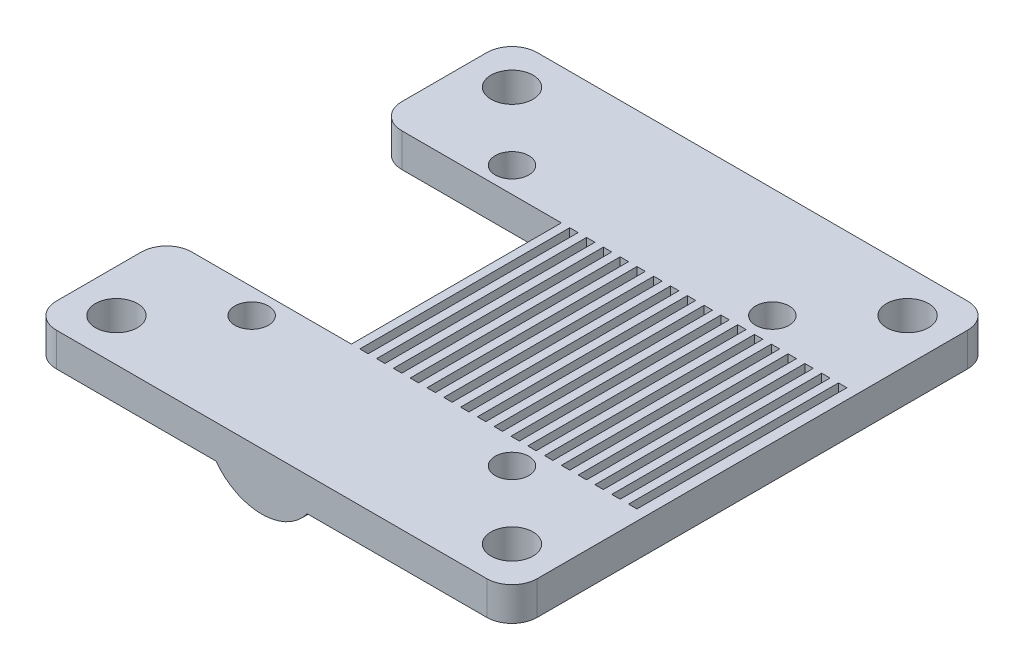
SolidWorks part; units mm, degrees
material "ABS"
ref_plane "Front Plane" through (0, 0, 0) normal (0, 0, 1) x (1, 0, 0)
ref_plane "Top Plane" through (0, 0, 0) normal (0, 1, 0) x (1, 0, 0)
ref_plane "Right Plane" through (0, 0, 0) normal (1, 0, 0) x (0, 0, -1)
sketch "Sketch1" plane through (0, 0, 0) normal (0, 1, 0) x (1, 0, 0)
  line L1 (25.625, 28.625) -> (-25.625, 28.625)
  line L2 (28.625, 25.625) -> (28.625, -25.625)
  line L3 (25.625, -28.625) -> (-25.625, -28.625)
  line L4 (-28.625, 25.625) -> (-28.625, -25.625)
  line L5 (28.625, 28.625) -> (-28.625, -28.625) construction
  line L6 (28.625, -28.625) -> (-28.625, 28.625) construction
  line L7 (23.55, -23.55) -> (-23.55, -23.55) construction
  line L8 (23.55, -23.55) -> (23.55, 23.55) construction
  line L9 (23.55, 23.55) -> (-23.55, 23.55) construction
  line L10 (-23.55, -23.55) -> (-23.55, 23.55) construction
  line L11 (23.55, -23.55) -> (-23.55, 23.55) construction
  line L12 (23.55, 23.55) -> (-23.55, -23.55) construction
  line L13 (15.5, 15.5) -> (-15.5, 15.5) construction
  line L14 (15.5, 15.5) -> (15.5, -15.5) construction
  line L15 (15.5, -15.5) -> (-15.5, -15.5) construction
  line L16 (-15.5, 15.5) -> (-15.5, -15.5) construction
  line L17 (15.5, 15.5) -> (-15.5, -15.5) construction
  line L18 (15.5, -15.5) -> (-15.5, 15.5) construction
  circle A0 centre (-15.5, 15.5) radius 2
  circle A1 centre (-23.55, 23.55) radius 2.5
  circle A2 centre (23.55, 23.55) radius 2.5
  circle A3 centre (15.5, 15.5) radius 2
  circle A4 centre (15.5, -15.5) radius 2
  circle A5 centre (-15.5, -15.5) radius 2
  circle A6 centre (-23.55, -23.55) radius 2.5
  circle A7 centre (23.55, -23.55) radius 2.5
  arc A8 (25.625, 28.625) -> (28.625, 25.625) centre (25.625, 25.625) cw
  arc A9 (28.625, -25.625) -> (25.625, -28.625) centre (25.625, -25.625) cw
  arc A10 (-25.625, -28.625) -> (-28.625, -25.625) centre (-25.625, -25.625) cw
  arc A11 (-25.625, 28.625) -> (-28.625, 25.625) centre (-25.625, 25.625) ccw
  point P0 (0, 0)
  point P5 (0, 0)
  point P11 (0, 0)
  dimension "D7" = 5
  dimension "D8" = 5
  dimension "D9" = 4
  dimension "D10" = 4
  dimension "D11" = 4
  dimension "D12" = 4
  dimension "D13" = 5
  dimension "D14" = 5
  dimension "D15" = 3
  dimension "D1" = 57.25
  dimension "D2" = 57.25
  dimension "D3" = 47.1
  dimension "D4" = 47.1
  dimension "D5" = 31
  dimension "D6" = 31
extrude "Boss-Extrude1" add sketch "Sketch1" along normal blind 4
sketch "Sketch2" plane through (0, 4, 0) normal (0, 1, 0) x (1, 0, 0)
  line L0 (-28.625, 25.625) -> (-28.625, -25.625) construction
  line L3 (-27.625, 12.5) -> (-26.625, 12.5)
  line L4 (-27.625, 12.5) -> (-27.625, -12.5)
  line L5 (-27.625, -12.5) -> (-26.625, -12.5)
  line L6 (-26.625, 12.5) -> (-26.625, -12.5)
  line L7 (-25.625, -12.5) -> (-24.625, -12.5)
  line L8 (-24.625, 12.5) -> (-24.625, -12.5)
  line L9 (-25.625, 12.5) -> (-25.625, -12.5)
  line L10 (-25.625, 12.5) -> (-24.625, 12.5)
  line L11 (-23.625, -12.5) -> (-22.625, -12.5)
  line L12 (-22.625, 12.5) -> (-22.625, -12.5)
  line L13 (-23.625, 12.5) -> (-23.625, -12.5)
  line L14 (-23.625, 12.5) -> (-22.625, 12.5)
  line L15 (-21.625, -12.5) -> (-20.625, -12.5)
  line L16 (-20.625, 12.5) -> (-20.625, -12.5)
  line L17 (-21.625, 12.5) -> (-21.625, -12.5)
  line L18 (-21.625, 12.5) -> (-20.625, 12.5)
  line L19 (-19.625, -12.5) -> (-18.625, -12.5)
  line L20 (-18.625, 12.5) -> (-18.625, -12.5)
  line L21 (-19.625, 12.5) -> (-19.625, -12.5)
  line L22 (-19.625, 12.5) -> (-18.625, 12.5)
  line L23 (-17.625, -12.5) -> (-16.625, -12.5)
  line L24 (-16.625, 12.5) -> (-16.625, -12.5)
  line L25 (-17.625, 12.5) -> (-17.625, -12.5)
  line L26 (-17.625, 12.5) -> (-16.625, 12.5)
  line L27 (-15.625, -12.5) -> (-14.625, -12.5)
  line L28 (-14.625, 12.5) -> (-14.625, -12.5)
  line L29 (-15.625, 12.5) -> (-15.625, -12.5)
  line L30 (-15.625, 12.5) -> (-14.625, 12.5)
  line L31 (-13.625, -12.5) -> (-12.625, -12.5)
  line L32 (-12.625, 12.5) -> (-12.625, -12.5)
  line L33 (-13.625, 12.5) -> (-13.625, -12.5)
  line L34 (-13.625, 12.5) -> (-12.625, 12.5)
  line L35 (-11.625, -12.5) -> (-10.625, -12.5)
  line L36 (-10.625, 12.5) -> (-10.625, -12.5)
  line L37 (-11.625, 12.5) -> (-11.625, -12.5)
  line L38 (-11.625, 12.5) -> (-10.625, 12.5)
  line L39 (-9.625, -12.5) -> (-8.625, -12.5)
  line L40 (-8.625, 12.5) -> (-8.625, -12.5)
  line L41 (-9.625, 12.5) -> (-9.625, -12.5)
  line L42 (-9.625, 12.5) -> (-8.625, 12.5)
  line L43 (-7.625, -12.5) -> (-6.625, -12.5)
  line L44 (-6.625, 12.5) -> (-6.625, -12.5)
  line L45 (-7.625, 12.5) -> (-7.625, -12.5)
  line L46 (-7.625, 12.5) -> (-6.625, 12.5)
  line L47 (-5.625, -12.5) -> (-4.625, -12.5)
  line L48 (-4.625, 12.5) -> (-4.625, -12.5)
  line L49 (-5.625, 12.5) -> (-5.625, -12.5)
  line L50 (-5.625, 12.5) -> (-4.625, 12.5)
  line L51 (-3.625, -12.5) -> (-2.625, -12.5)
  line L52 (-2.625, 12.5) -> (-2.625, -12.5)
  line L53 (-3.625, 12.5) -> (-3.625, -12.5)
  line L54 (-3.625, 12.5) -> (-2.625, 12.5)
  line L55 (-1.625, -12.5) -> (-0.625, -12.5)
  line L56 (-0.625, 12.5) -> (-0.625, -12.5)
  line L57 (-1.625, 12.5) -> (-1.625, -12.5)
  line L58 (-1.625, 12.5) -> (-0.625, 12.5)
  line L59 (0.375, -12.5) -> (1.375, -12.5)
  line L60 (1.375, 12.5) -> (1.375, -12.5)
  line L61 (0.375, 12.5) -> (0.375, -12.5)
  line L62 (0.375, 12.5) -> (1.375, 12.5)
  line L63 (2.375, -12.5) -> (3.375, -12.5)
  line L64 (3.375, 12.5) -> (3.375, -12.5)
  line L65 (2.375, 12.5) -> (2.375, -12.5)
  line L66 (2.375, 12.5) -> (3.375, 12.5)
  line L67 (4.375, -12.5) -> (5.375, -12.5)
  line L68 (5.375, 12.5) -> (5.375, -12.5)
  line L69 (4.375, 12.5) -> (4.375, -12.5)
  line L70 (4.375, 12.5) -> (5.375, 12.5)
  line L71 (6.375, -12.5) -> (7.375, -12.5)
  line L72 (7.375, 12.5) -> (7.375, -12.5)
  line L73 (6.375, 12.5) -> (6.375, -12.5)
  line L74 (6.375, 12.5) -> (7.375, 12.5)
  line L75 (8.375, -12.5) -> (9.375, -12.5)
  line L76 (9.375, 12.5) -> (9.375, -12.5)
  line L77 (8.375, 12.5) -> (8.375, -12.5)
  line L78 (8.375, 12.5) -> (9.375, 12.5)
  line L79 (10.375, -12.5) -> (11.375, -12.5)
  line L80 (11.375, 12.5) -> (11.375, -12.5)
  line L81 (10.375, 12.5) -> (10.375, -12.5)
  line L82 (10.375, 12.5) -> (11.375, 12.5)
  line L83 (12.375, -12.5) -> (13.375, -12.5)
  line L84 (13.375, 12.5) -> (13.375, -12.5)
  line L85 (12.375, 12.5) -> (12.375, -12.5)
  line L86 (12.375, 12.5) -> (13.375, 12.5)
  line L87 (14.375, -12.5) -> (15.375, -12.5)
  line L88 (15.375, 12.5) -> (15.375, -12.5)
  line L89 (14.375, 12.5) -> (14.375, -12.5)
  line L90 (14.375, 12.5) -> (15.375, 12.5)
  line L91 (16.375, -12.5) -> (17.375, -12.5)
  line L92 (17.375, 12.5) -> (17.375, -12.5)
  line L93 (16.375, 12.5) -> (16.375, -12.5)
  line L94 (16.375, 12.5) -> (17.375, 12.5)
  line L95 (18.375, -12.5) -> (19.375, -12.5)
  line L96 (19.375, 12.5) -> (19.375, -12.5)
  line L97 (18.375, 12.5) -> (18.375, -12.5)
  line L98 (18.375, 12.5) -> (19.375, 12.5)
  line L99 (20.375, -12.5) -> (21.375, -12.5)
  line L100 (21.375, 12.5) -> (21.375, -12.5)
  line L101 (20.375, 12.5) -> (20.375, -12.5)
  line L102 (20.375, 12.5) -> (21.375, 12.5)
  line L103 (22.375, -12.5) -> (23.375, -12.5)
  line L104 (23.375, 12.5) -> (23.375, -12.5)
  line L105 (22.375, 12.5) -> (22.375, -12.5)
  line L106 (22.375, 12.5) -> (23.375, 12.5)
  line L107 (24.375, -12.5) -> (25.375, -12.5)
  line L108 (25.375, 12.5) -> (25.375, -12.5)
  line L109 (24.375, 12.5) -> (24.375, -12.5)
  line L110 (24.375, 12.5) -> (25.375, 12.5)
  line L111 (26.375, -12.5) -> (27.375, -12.5)
  line L112 (27.375, 12.5) -> (27.375, -12.5)
  line L113 (26.375, 12.5) -> (26.375, -12.5)
  line L114 (26.375, 12.5) -> (27.375, 12.5)
  dimension "D1" = 1
  dimension "D2" = 1
  dimension "D3" = 12.5
  dimension "D4" = 25
  dimension "D5" = 28
extrude "Cut-Extrude1" cut sketch "Sketch2" against normal blind 1
sketch "Sketch3" plane through (0, 0, 0) normal (0, -1, 0) x (1, 0, 0)
  line L0 (-28.625, -25.625) -> (-28.625, 25.625) construction
  line L1 (-28.625, -12.5) -> (-6.625, -12.5)
  line L2 (-28.625, -12.5) -> (-28.625, 12.5)
  line L3 (-28.625, 12.5) -> (-6.625, 12.5)
  line L4 (-6.625, -12.5) -> (-6.625, 12.5)
  dimension "D1" = 25
  dimension "D2" = 22
  dimension "D3" = 12.5
extrude "Cut-Extrude2" cut sketch "Sketch3" against normal through all
sketch "Sketch4" plane through (0, 0, -28.625) normal (0, 0, -1) x (-1, 0, 0)
  line L1 (-4.2493, 0) -> (6.625, 0)
  line L3 (-25.625, 0) -> (25.625, 0) construction
  line L4 (-25.625, 4) -> (25.625, 4) construction
  arc A0 (-4.2493, 0) -> (6.625, 0) centre (1.1879, 4) ccw
  dimension "D1" = 13.5
  dimension "D2" = 22
extrude "Boss-Extrude2" add sketch "Sketch4" against normal up to surface (57.25 mm away) up to face at (0, 2, 28.625)
fillet "Fillet1" radius 3 2 edges at (-28.625, 2, 12.5) (-28.625, 2, -12.5)
